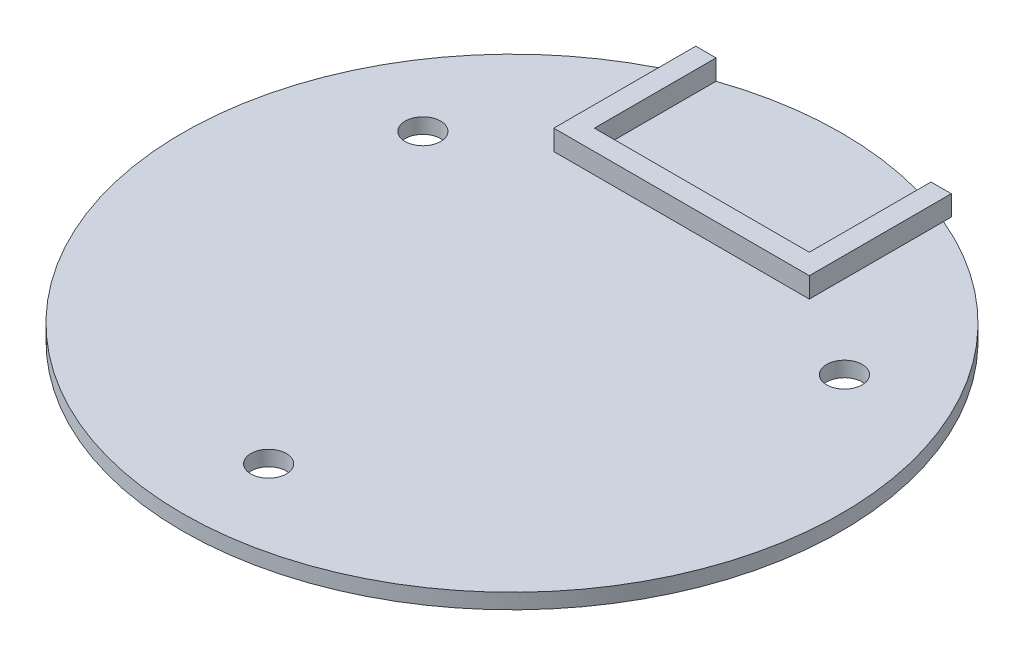
SolidWorks part; units mm, degrees
ref_plane "前视基准面" through (0, 0, 0) normal (0, 0, 1) x (1, 0, 0)
ref_plane "上视基准面" through (0, 0, 0) normal (0, 1, 0) x (1, 0, 0)
ref_plane "右视基准面" through (0, 0, 0) normal (1, 0, 0) x (0, 0, -1)
sketch "草图1" plane through (0, 0, 0) normal (0, 1, 0) x (1, 0, 0)
  circle A0 centre (0, 0) radius 32.5
  dimension "D1" = 65
extrude "凸台-拉伸1" add sketch "草图1" along normal blind 1.5
sketch "草图2" plane through (0, 0, 0) normal (0, -1, 0) x (1, 0, 0)
  circle A1 centre (0, 24) radius 1.75
  point P2 (0, 0)
  dimension "D2" = 3.5
  dimension "D1" = 24
sketch "草图4" plane through (0, 1.5, 0) normal (0, 1, 0) x (1, 0, 0)
  line L0 (-12.6, 30.7228) -> (-12.6, 16.7228)
  line L9 (-10.6, 30.7228) -> (10.6, 30.7228) construction
  line L10 (-10.6, 30.7228) -> (-10.6, 18.7228)
  line L11 (-10.6, 18.7228) -> (10.6, 18.7228)
  line L12 (10.6, 30.7228) -> (10.6, 18.7228)
  line L17 (-12.6, 16.7228) -> (12.6, 16.7228)
  line L22 (12.6, 30.7228) -> (12.6, 16.7228)
  line L23 (-10.6, 30.7228) -> (-12.6, 30.7228)
  line L24 (10.6, 30.7228) -> (12.6, 30.7228)
  circle A1 centre (0, 0) radius 32.5 construction
  dimension "D3" = 2
  dimension "D1" = 21.2
  dimension "D2" = 12
extrude "凸台-拉伸4" add sketch "草图4" along normal blind 2
extrude "切除-拉伸1" cut sketch "草图2" against normal blind 7
pattern_circular "阵列(圆周)1" count 3 every 120 about axis through (0, 0, 0) along (0, 1, 0) of "切除-拉伸1"
